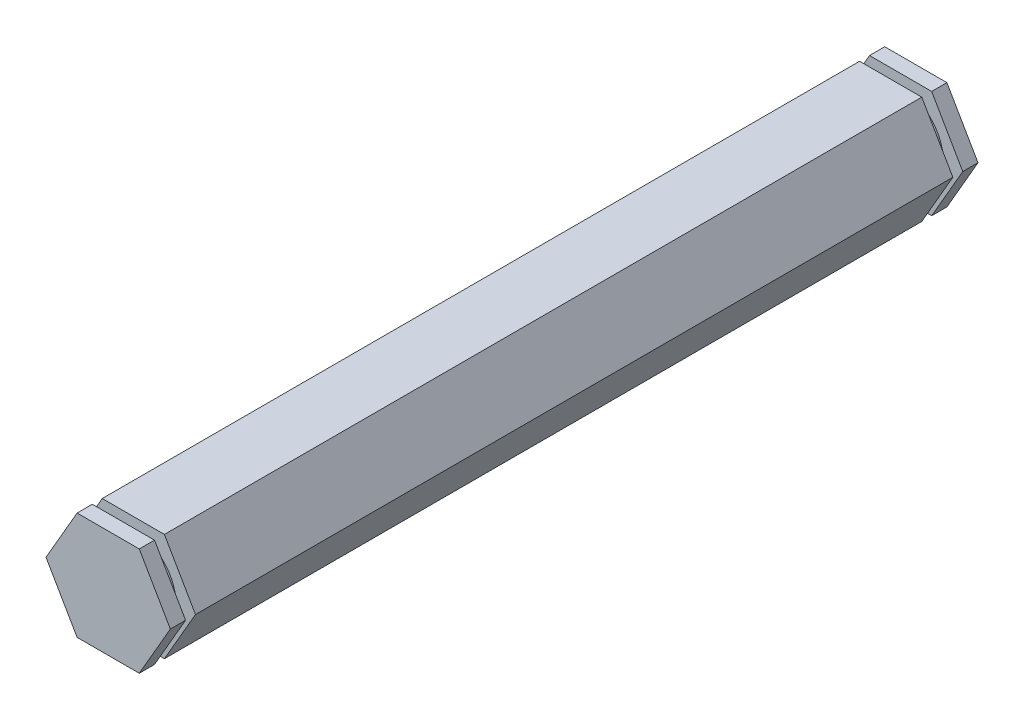
SolidWorks part; units mm, degrees
material "7075-T6 (SN)"
ref_plane "Front Plane" through (0, 0, 0) normal (0, 0, 1) x (1, 0, 0)
ref_plane "Top Plane" through (0, 0, 0) normal (0, 1, 0) x (1, 0, 0)
ref_plane "Right Plane" through (0, 0, 0) normal (1, 0, 0) x (0, 0, -1)
sketch "Sketch1" plane through (0, 0, 0) normal (0, 0, 1) x (1, 0, 0)
  line L1 (-3.6662, 6.35) -> (-7.3323, 0)
  line L2 (-7.3323, 0) -> (-3.6662, -6.35)
  line L3 (-3.6662, -6.35) -> (3.6662, -6.35)
  line L4 (3.6662, -6.35) -> (7.3323, 0)
  line L5 (7.3323, 0) -> (3.6662, 6.35)
  line L6 (3.6662, 6.35) -> (-3.6662, 6.35)
  circle A0 centre (0, 0) radius 6.35 construction
  dimension "D1" = 12.7
extrude "Boss-Extrude1" add sketch "Sketch1" along normal mid plane 95.25
sketch "Sketch2" plane through (0, 0, 0) normal (1, 0, 0) x (0, 0, -1)
  line L0 (-45.828, 7.7624) -> (-45.828, 5.0292)
  line L2 (-45.828, 5.0292) -> (-44.6595, 5.0292)
  line L3 (-44.6595, 5.0292) -> (-44.6595, 7.7624)
  line L4 (-45.2437, 5.0292) -> (-45.2437, -5.0292) construction
  line L5 (0, 0) -> (-6.1043, 0) construction
  line L6 (-47.625, 0) -> (47.625, 0) construction
  line L8 (-45.828, 7.7624) -> (-44.6595, 7.7624)
  point P8 (-45.2437, 0)
  dimension "D1" = 10.0584
  dimension "D2" = 1.1684
  dimension "D3" = 45.2437
revolve "Cut-Revolve1" cut sketch "Sketch2" angle 360 about L5
mirror "Mirror1" about plane through (0, 0, 0) normal (0, 0, 1) of "Cut-Revolve1"
